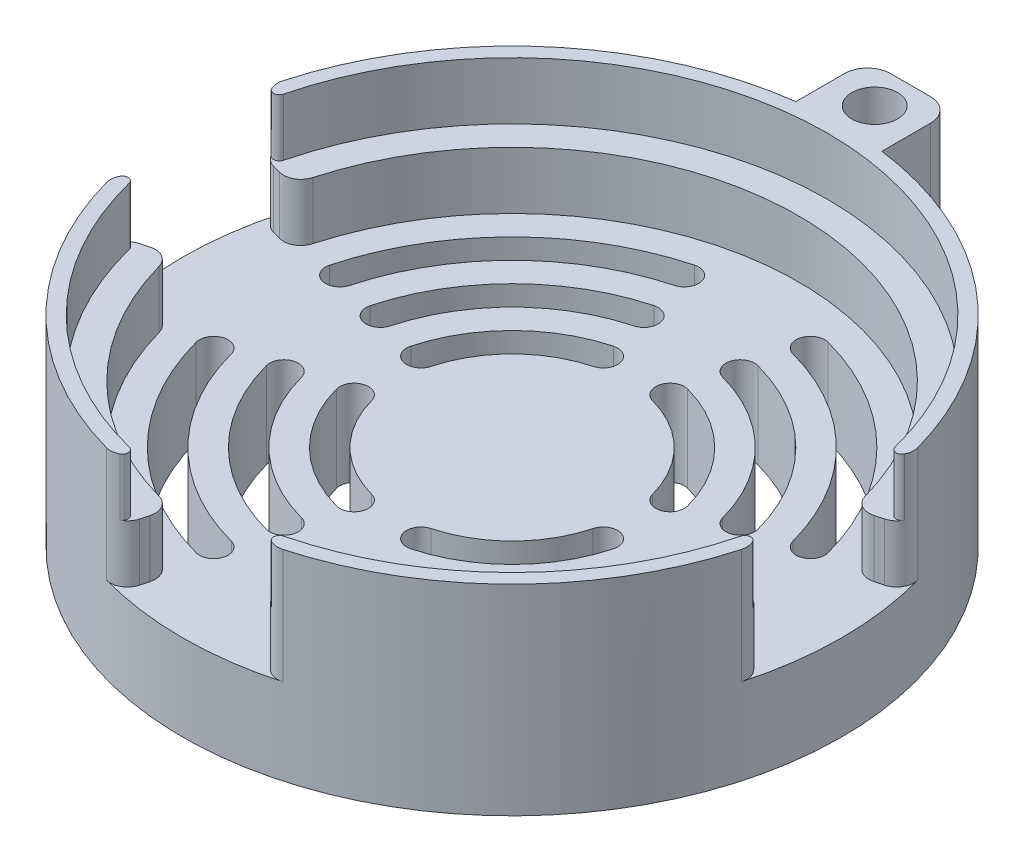
SolidWorks part; units mm, degrees
ref_plane "Alzado" through (0, 0, 0) normal (0, 0, 1) x (1, 0, 0)
ref_plane "Planta" through (0, 0, 0) normal (0, 1, 0) x (1, 0, 0)
ref_plane "Vista lateral" through (0, 0, 0) normal (1, 0, 0) x (0, 0, -1)
sketch "Croquis1" plane through (0, 0, 0) normal (0, 1, 0) x (1, 0, 0)
  circle A0 centre (0, 0) radius 57.5
  dimension "D1" = 115
extrude "Saliente-Extruir1" add sketch "Croquis1" along normal blind 35
sketch "Croquis2" plane through (0, 35, 0) normal (0, 1, 0) x (1, 0, 0)
  circle A0 centre (0, 0) radius 50
  dimension "D1" = 100
extrude "Cortar-Extruir1" cut sketch "Croquis2" against normal blind 20
sketch "Croquis3" plane through (0, 35, 0) normal (0, 1, 0) x (1, 0, 0)
  line L0 (0, 0) -> (0, 57.5) construction
  line L3 (-7.5, 57.0088) -> (-7.5, 69.5)
  line L4 (-7.5, 69.5) -> (7.5, 69.5)
  line L5 (7.5, 57.0088) -> (7.5, 69.5)
  circle A0 centre (0, 0) radius 57.5 construction
  arc A1 (7.5, 57.0088) -> (-7.5, 57.0088) centre (0, 0) ccw
  point P6 (0, 69.5)
  dimension "D1" = 12
  dimension "D2" = 15
extrude "Saliente-Extruir2" add sketch "Croquis3" against normal up to surface (35 mm away) up to face at (0, 0, 57.5)
fillet "Redondeo1" radius 4 2 edges at (7.5, 17.5, -69.5) (-7.5, 17.5, -69.5)
sketch "Croquis4" plane through (0, 35, 0) normal (0, 1, 0) x (1, 0, 0)
  circle A0 centre (0, 0) radius 55
  dimension "D1" = 110
extrude "Cortar-Extruir2" cut sketch "Croquis4" against normal blind 10
sketch "Croquis5" plane through (0, 15, 0) normal (0, 1, 0) x (1, 0, 0)
  line L0 (-1000, 0) -> (49000, 0) construction
  line L1 (0, -1000) -> (0, -30) construction
  line L2 (0, 0) -> (-24.6307, 91.923) construction
  line L3 (0, 0) -> (-48.2963, 12.941) construction
  line L4 (0, 0) -> (0, 49000) construction
  arc A2 (-5.1764, 19.3185) -> (-6.4705, 24.1481) centre (-5.8234, 21.7333) ccw
  arc A7 (-19.3185, 5.1764) -> (-24.1481, 6.4705) centre (-21.7333, 5.8234) cw
  arc A14 (-5.1764, 19.3185) -> (-19.3185, 5.1764) centre (0, 0) ccw
  arc A15 (-6.4705, 24.1481) -> (-24.1481, 6.4705) centre (0, 0) ccw
  circle A17 centre (0, 0) radius 50 construction
  arc A18 (-7.7646, 28.9778) -> (-28.9778, 7.7646) centre (0, 0) ccw
  arc A19 (-9.0587, 33.8074) -> (-33.8074, 9.0587) centre (0, 0) ccw
  arc A20 (-7.7646, 28.9778) -> (-9.0587, 33.8074) centre (-8.4116, 31.3926) ccw
  arc A21 (-33.8074, 9.0587) -> (-28.9778, 7.7646) centre (-31.3926, 8.4116) ccw
  arc A24 (-11.6469, 43.4667) -> (-43.4667, 11.6469) centre (0, 0) ccw
  arc A25 (-10.3528, 38.637) -> (-38.637, 10.3528) centre (0, 0) ccw
  arc A27 (-10.3528, 38.637) -> (-11.6469, 43.4667) centre (-10.9998, 41.0518) ccw
  arc A28 (-43.4667, 11.6469) -> (-38.637, 10.3528) centre (-41.0518, 10.9998) ccw
  dimension "D1" = 20
  dimension "D2" = 2.5
  dimension "D4" = 5
  dimension "D6" = 60
  dimension "D7" = 70
  dimension "D8" = 5
  dimension "D9" = 5
  dimension "D10" = 40
  dimension "D11" = 45
  dimension "D12" = 2.5
  dimension "D13" = 5
  dimension "D3" = 15
  dimension "D5" = 15
extrude "Cortar-Extruir3" cut sketch "Croquis5" against normal through all
pattern_circular "MatrizC1" count 4 over 360 about axis through (0, 0, 0) along (0, 1, 0) of "Cortar-Extruir3"
sketch "Croquis6" plane through (0, 35, 0) normal (0, 1, 0) x (1, 0, 0)
  line L0 (-71.1616, 16.4795) -> (-16.6363, 1.8695)
  line L1 (-15.7802, -1.6401) -> (-63.5779, -14.4475)
  line L2 (-15.7802, -1.6401) -> (-16.6363, 1.8695)
  line L3 (-63.5779, -14.4475) -> (-71.1616, 16.4795)
  arc A0 (-43.4667, 11.6469) -> (-38.637, 10.3528) centre (-41.0518, 10.9998) ccw construction
  arc A1 (-24.1481, 6.4705) -> (-19.3185, 5.1764) centre (-21.7333, 5.8234) ccw construction
  arc A2 (-19.3185, -5.1764) -> (-24.1481, -6.4705) centre (-21.7333, -5.8234) ccw construction
  arc A3 (-38.637, -10.3528) -> (-43.4667, -11.6469) centre (-41.0518, -10.9998) ccw construction
extrude "Cortar-Extruir4" cut sketch "Croquis6" against normal up to surface (20 mm away) up to face at (-27.597, 15, 27.597)
fillet "Redondeo2" radius 3 2 edges at (-48.8829, 20, -10.51) (-56.1353, 25, -12.4532)
fillet "Redondeo3" radius 3 2 edges at (-48.8829, 20, 10.51) (-56.1353, 25, 12.4532)
fillet "Redondeo4" radius 1 2 edges at (-53.7109, 30, 11.8383) (-53.7109, 30, -11.8383)
pattern_circular "MatrizC2" count 3 over 180 about axis through (0, 0, 0) along (0, 1, 0) of "Cortar-Extruir4", "Redondeo2", "Redondeo3", "Redondeo4"
sketch "Croquis7" plane through (0, 35, 0) normal (0, 1, 0) x (1, 0, 0)
  line L1 (-7.5, 69.5) -> (-7.5, 65.5) construction
  line L2 (7.5, 65.5) -> (7.5, 69.5) construction
  line L3 (-7.5, 69.5) -> (7.5, 69.5) construction
  line L5 (-7.5, 69.5) -> (7.5, 57.0088) construction
  line L6 (7.5, 69.5) -> (-7.5, 57.0088) construction
  circle A0 centre (0, 63.2544) radius 4
  arc A1 (-7.5, 57.0088) -> (-55.4019, 15.391) centre (0, 0) ccw construction
  point P7 (0, 63.2544)
  point P12 (0, 69.5)
  point P18 (-4.9004, 57.2908)
  point P19 (-7.5, 57.0088)
  point P20 (-7.5, 57.0088)
  point P21 (-7.5, 57.0088)
  dimension "D1" = 8
extrude "Cortar-Extruir5" cut sketch "Croquis7" against normal through all contours A0
